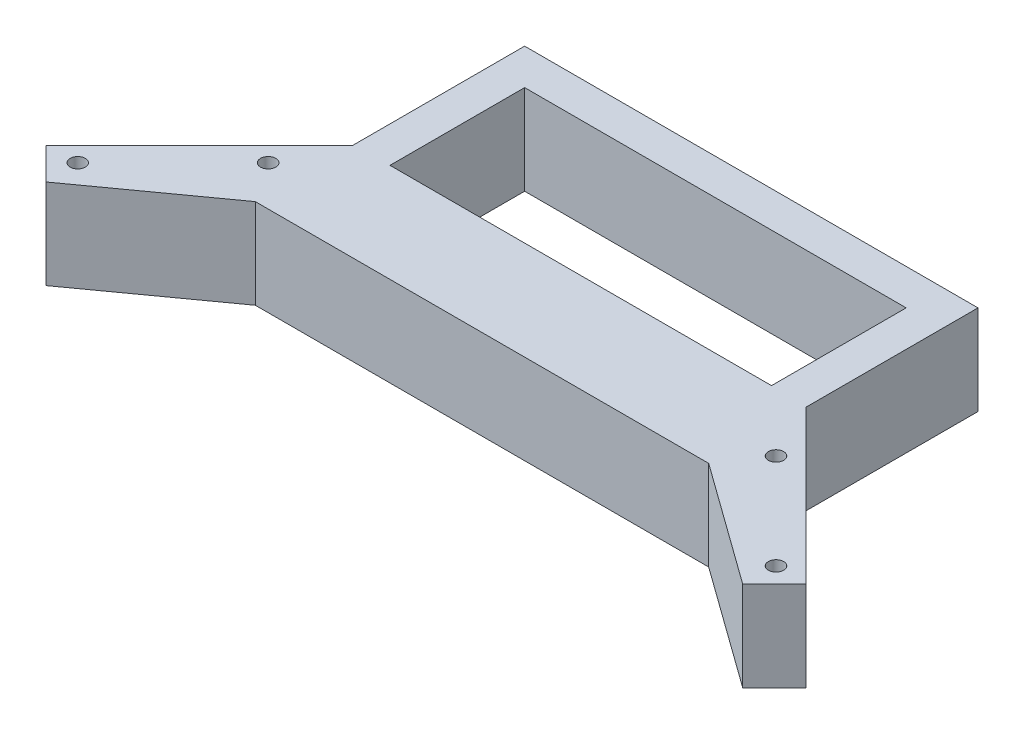
SolidWorks part; units mm, degrees
ref_plane "Front Plane" through (0, 0, 0) normal (0, 0, 1) x (1, 0, 0)
ref_plane "Top Plane" through (0, 0, 0) normal (0, 1, 0) x (1, 0, 0)
ref_plane "Right Plane" through (0, 0, 0) normal (1, 0, 0) x (0, 0, -1)
sketch "Sketch3" plane through (0, 0, 0) normal (0, 1, 0) x (1, 0, 0)
  line L0 (-64.135, -22.5658) -> (-107.5475, -65.9783)
  line L1 (-50.8, -12.7) -> (50.8, -12.7)
  line L2 (-50.8, -12.7) -> (-50.8, 12.7)
  line L3 (-50.8, 12.7) -> (50.8, 12.7)
  line L4 (50.8, -12.7) -> (50.8, 12.7)
  line L5 (-50.8, -12.7) -> (50.8, 12.7) construction
  line L6 (-50.8, 12.7) -> (50.8, -12.7) construction
  line L7 (-53.975, 15.875) -> (53.975, 15.875)
  line L8 (-53.975, 15.875) -> (-53.975, -22.225)
  line L9 (-53.975, -22.225) -> (53.975, -22.225)
  line L10 (53.975, 15.875) -> (53.975, -22.225)
  line L11 (-64.135, 26.035) -> (64.135, 26.035)
  line L12 (-64.135, 26.035) -> (-64.135, -50.165)
  line L13 (-64.135, -50.165) -> (64.135, -50.165)
  line L14 (64.135, 26.035) -> (64.135, -50.165)
  line L15 (-107.5475, -65.9783) -> (-98.5673, -74.9586)
  line L16 (-98.7828, -65.7628) -> (0, 33.02)
  line L17 (0, 33.02) -> (98.7828, -65.7628)
  line L18 (-98.7828, -65.7628) -> (0, -164.5456)
  line L19 (0, -164.5456) -> (98.7828, -65.7628)
  line L20 (-98.5673, -74.9586) -> (-64.135, -50.165)
  line L21 (64.135, -22.5658) -> (107.5475, -65.9783)
  line L22 (107.5475, -65.9783) -> (98.5673, -74.9586)
  line L23 (98.5673, -74.9586) -> (64.135, -50.165)
  circle A4 centre (-98.7828, -65.7628) radius 2.159
  circle A5 centre (-71.842, -38.822) radius 2.159
  circle A6 centre (98.7828, -65.7628) radius 2.159
  circle A7 centre (71.842, -38.822) radius 2.159
  point P0 (0, 0)
  point P16 (-80.8223, -47.8023)
  point P18 (-89.8026, -56.7826)
  point P19 (-71.842, -38.822)
  dimension "D26" = 4.318
  dimension "D27" = 4.318
  dimension "D28" = 4.318
  dimension "D29" = 4.318
  dimension "D1" = 101.6
  dimension "D2" = 25.4
  dimension "D3" = 3.175
  dimension "D4" = 3.175
  dimension "D5" = 38.1
  dimension "D6" = 3.175
  dimension "D7" = 10.16
  dimension "D8" = 10.16
  dimension "D9" = 10.16
  dimension "D10" = 139.7
  dimension "D11" = 139.7
  dimension "D12" = 139.7
  dimension "D13" = 139.7
  dimension "D14" = 33.02
  dimension "D15" = 12.7
  dimension "D16" = 12.7
  dimension "D17" = 12.7
  dimension "D18" = 76.2
  dimension "D19" = 45
  dimension "D20" = 6.0452
  dimension "D21" = 6.35
  dimension "D22" = 12.7
  dimension "D23" = 6.0452
  dimension "D24" = 6.35
  dimension "D25" = 12.7
  dimension "D30" = 38.1
extrude "Boss-Extrude1" add sketch "Sketch3" along normal blind 25.4 contours L17 L10 L9 L8 L16 L12 L13 L14 | L12 L16 L8 L7 L11 | L17 L11 L16 L7 | L11 L17 L7 L10 L14 | A7 L17 A6 L19 L23 L22 L21 L14 | A7 L17 L14 L23 L19 A6 | A5 L16 A4 L18 L20 L12 | A5 L16 L12 L0 L15 L20 L18 A4
ref_plane "Plane1" through (0, 0, 22.225) normal (0, 0, -1) x (-1, 0, 0)
sketch "Sketch4" plane through (0, 0, 22.225) normal (0, 0, -1) x (-1, 0, 0)
  line L0 (-41.25, 29.45) -> (16.75, 29.45)
  line L1 (-41.25, 29.45) -> (-41.25, -4.05)
  line L2 (-41.25, -4.05) -> (16.75, -4.05)
  line L3 (16.75, 29.45) -> (16.75, -4.05)
  line L4 (-53.975, 0) -> (53.975, 0)
  line L5 (53.975, 0) -> (53.975, 25.4)
  line L6 (53.975, 25.4) -> (-53.975, 25.4)
  line L7 (-53.975, 25.4) -> (-53.975, 0)
  line L8 (-53.975, 0) -> (53.975, 0)
  line L9 (53.975, 0) -> (53.975, 25.4)
  line L10 (53.975, 25.4) -> (-53.975, 25.4)
  line L11 (-53.975, 25.4) -> (-53.975, 0)
  line L12 (-15, 27.2) -> (15, 27.2)
  line L13 (-15, 27.2) -> (-15, -1.8)
  line L14 (-15, -1.8) -> (15, -1.8)
  line L15 (15, 27.2) -> (15, -1.8)
  line L16 (-15, 27.2) -> (15, -1.8) construction
  line L17 (-15, -1.8) -> (15, 27.2) construction
  line L19 (-43.65, 25.4) -> (-43.65, -6.45)
  line L20 (-43.65, -6.45) -> (19.15, -6.45)
  line L22 (-41.25, 118.35) -> (16.75, 118.35)
  line L23 (-41.25, 118.35) -> (-41.25, 84.85)
  line L24 (-41.25, 84.85) -> (16.75, 84.85)
  line L25 (16.75, 118.35) -> (16.75, 84.85)
  line L26 (-15, 116.1) -> (15, 116.1)
  line L27 (-15, 116.1) -> (-15, 87.1)
  line L28 (-15, 87.1) -> (15, 87.1)
  line L29 (15, 116.1) -> (15, 87.1)
  line L30 (-15, 116.1) -> (15, 87.1) construction
  line L31 (-15, 87.1) -> (15, 116.1) construction
  line L32 (-43.65, 120.75) -> (19.15, 120.75)
  line L38 (19.15, 25.4) -> (19.15, -6.45)
  line L39 (-43.65, 120.75) -> (-43.65, 25.4)
  line L40 (19.15, 120.75) -> (19.15, 25.4)
  circle A0 centre (-25.05, 12.7) radius 4.25
  circle A1 centre (-26.8, 12.7) radius 6
  circle A2 centre (-26.8, 12.7) radius 6.5
  circle A3 centre (-25.05, 101.6) radius 4.25
  circle A4 centre (-26.8, 101.6) radius 6
  circle A5 centre (-26.8, 101.6) radius 6.5
  point P2 (0, 12.7)
  point P12 (0, 12.7)
  point P13 (0, 12.7)
  point P14 (-25.05, 12.7)
  point P33 (0, 101.6)
  point P34 (0, 101.6)
  point P35 (-25.05, 101.6)
  dimension "D10" = 8.5
  dimension "D11" = 12
  dimension "D16" = 13
  dimension "D25" = 8.5
  dimension "D26" = 12
  dimension "D31" = 13
  dimension "D2" = 33.5
  dimension "D3" = 58
  dimension "D4" = 16.75
  dimension "D5" = 16.75
  dimension "D6" = 16.2
  dimension "D7" = 16.75
  dimension "D8" = 30
  dimension "D9" = 29
  dimension "D14" = 2.4
  dimension "D15" = 2.4
  dimension "D17" = 33.5
  dimension "D18" = 58
  dimension "D19" = 16.75
  dimension "D20" = 16.75
  dimension "D21" = 16.2
  dimension "D22" = 16.75
  dimension "D23" = 30
  dimension "D24" = 29
  dimension "D27" = 2.4
  dimension "D32" = 88.9
  dimension "D1" = 0
ref_plane "Plane2" through (0, 0, 1.905) normal (0, 0, -1) x (-1, 0, 0)
sketch "Sketch5" plane through (0, 0, 1.905) normal (0, 0, -1) x (-1, 0, 0)
  circle A0 centre (0, 12.7) radius 50.8
  dimension "D1" = 101.6
